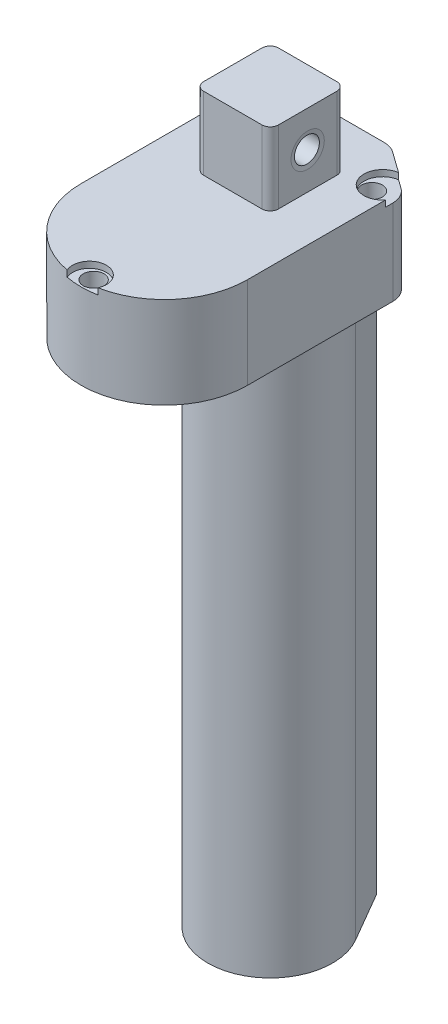
SolidWorks part; units mm, degrees
ref_plane "Alzado" through (0, 0, 0) normal (0, 0, 1) x (1, 0, 0)
ref_plane "Planta" through (0, 0, 0) normal (0, 1, 0) x (1, 0, 0)
ref_plane "Vista lateral" through (0, 0, 0) normal (1, 0, 0) x (0, 0, -1)
sketch "Croquis2" plane through (0, 0, 0) normal (0, 1, 0) x (1, 0, 0)
  line L0 (-17.9062, 38.9956) -> (-10.8039, 44.0687)
  line L1 (0, 0) -> (0, -20) construction
  line L2 (-20, 0) -> (-20, 34.9269)
  line L3 (-7.8977, 45) -> (7.8977, 45)
  line L4 (20, 0) -> (20, 34.9269)
  line L19 (10.8039, 44.0687) -> (17.9062, 38.9956)
  arc A0 (-20, 0) -> (20, 0) centre (0, 0) ccw
  arc A1 (-20, 34.9269) -> (-17.9062, 38.9956) centre (-15, 34.9269) cw
  arc A2 (17.9062, 38.9956) -> (20, 34.9269) centre (15, 34.9269) cw
  arc A3 (10.8039, 44.0687) -> (7.8977, 45) centre (7.8977, 40) ccw
  arc A4 (-7.8977, 45) -> (-10.8039, 44.0687) centre (-7.8977, 40) ccw
  point P1 (0, 45)
  dimension "D1" = 5
  dimension "D2" = 20
  dimension "D3" = 5
  dimension "D4" = 5
  dimension "D5" = 65
extrude "Saliente-Extruir1" add sketch "Croquis2" along normal blind 22
sketch "Croquis3" plane through (0, 22, 0) normal (0, 1, 0) x (1, 0, 0)
  circle A0 centre (-15, 34.9269) radius 2.5
  circle A1 centre (15, 34.9269) radius 2.5
  circle A2 centre (-16.5, 36) radius 4.5
  circle A3 centre (16.5, 36) radius 4.5
extrude "Cortar-Extruir2" cut sketch "Croquis3" against normal blind 1.5
sketch "Croquis4" plane through (0, 22, 0) normal (0, 1, 0) x (1, 0, 0)
  circle A0 centre (-15, 34.9269) radius 2.5
  circle A1 centre (15, 34.9269) radius 2.5
extrude "Cortar-Extruir3" cut sketch "Croquis4" against normal blind 18
sketch "Croquis5" plane through (0, 22, 0) normal (0, 1, 0) x (1, 0, 0)
  line L0 (0, -20) -> (0, -17)
  arc A0 (-20, 0) -> (20, 0) centre (0, 0) ccw construction
  circle A1 centre (0, -17) radius 2.5
  circle A3 centre (0.022, -18) radius 4.0586
extrude "Cortar-Extruir4" cut sketch "Croquis5" against normal blind 1.5 contours A3
sketch "Croquis6" plane through (0, 20.5, 0) normal (0, 1, 0) x (1, 0, 0)
  circle A1 centre (0.0245, -17) radius 2.5
extrude "Cortar-Extruir5" cut sketch "Croquis6" against normal blind 15
sketch "Croquis7" plane through (0, 20.5, 0) normal (0, 1, 0) x (1, 0, 0)
  line L0 (0.0245, -20) -> (0.0245, -16.2667) construction
  line L2 (7.0037, 16.4602) -> (-7.0037, 16.4602)
  line L3 (9.0037, 18.4602) -> (9.0037, 32.4653)
  line L4 (7.0037, 34.4653) -> (-7.0037, 34.4653)
  line L5 (-9.0037, 18.4602) -> (-9.0037, 32.4653)
  line L6 (9.0037, 16.4602) -> (-9.0037, 34.4653) construction
  line L11 (9.0037, 34.4653) -> (-9.0037, 16.4602) construction
  arc A0 (-3.6825, -19.6581) -> (3.7305, -19.649) centre (0, 0) ccw construction
  arc A1 (-9.0037, 18.4602) -> (-7.0037, 16.4602) centre (-7.0037, 18.4602) ccw
  arc A2 (9.0037, 18.4602) -> (7.0037, 16.4602) centre (7.0037, 18.4602) cw
  arc A3 (7.0037, 34.4653) -> (9.0037, 32.4653) centre (7.0037, 32.4653) cw
  arc A4 (-7.0037, 34.4653) -> (-9.0037, 32.4653) centre (-7.0037, 32.4653) ccw
  point P5 (0, 25.4628)
  point P28 (0, 25.4628)
  dimension "D1" = 2
extrude "Saliente-Extruir2" add sketch "Croquis7" along normal blind 19
sketch "Croquis8" plane through (-9.0037, 0, 0) normal (-1, 0, 0) x (0, 0, 1)
  line L0 (-25.4628, 39.5) -> (-25.4628, 22) construction
  line L1 (-32.4653, 39.5) -> (-18.4602, 39.5) construction
  line L2 (-18.4602, 22) -> (-32.4653, 22) construction
  line L3 (-32.4653, 30.75) -> (-18.4602, 30.75) construction
  line L4 (-32.4653, 39.5) -> (-32.4653, 22) construction
  line L5 (-18.4602, 39.5) -> (-18.4602, 22) construction
  circle A1 centre (-25.4628, 30.75) radius 3
extrude "Cortar-Extruir7" cut sketch "Croquis8" against normal blind 19
sketch "Croquis9" plane through (-9.0037, 0, 0) normal (-1, 0, 0) x (0, 0, 1)
  circle A0 centre (-25.4628, 30.75) radius 4
extrude "Cortar-Extruir10" cut sketch "Croquis9" against normal blind 0.5 draft 80
sketch "Croquis10" plane through (9.0037, 0, 0) normal (1, 0, 0) x (0, 0, -1)
  circle A0 centre (25.4628, 30.75) radius 4
extrude "Cortar-Extruir11" cut sketch "Croquis10" against normal blind 0.5 draft 80
sketch "Croquis11" plane through (0, 0, 0) normal (0, -1, 0) x (1, 0, 0)
  line L0 (0, 0) -> (0, -50.9255) construction
  line L1 (-20, -34.9269) -> (-20, 0) construction
  line L2 (0, -16.4602) -> (0, -34.4653) construction
  line L4 (-6, -45) -> (-12.9713, -32.9957)
  line L5 (-6, -45) -> (6, -45)
  line L6 (6, -45) -> (12.9713, -32.9957)
  line L7 (7.0037, -16.4602) -> (-7.0037, -16.4602) construction
  line L8 (7.8977, -45) -> (-7.8977, -45) construction
  line L9 (-7.0037, -34.4653) -> (7.0037, -34.4653) construction
  line L10 (-9.0037, -25.4628) -> (8.8273, -25.4628) construction
  line L11 (-9.0037, -18.4602) -> (-9.0037, -32.4653) construction
  line L12 (8.8273, -28.4628) -> (8.8273, -22.4628) construction
  arc A1 (12.9713, -32.9957) -> (-12.9713, -32.9957) centre (0, -25.4628) ccw
  dimension "D1" = 12
  dimension "D2" = 30
  dimension "D3" = 0
  dimension "D4" = 20
  dimension "D5" = 6
extrude "Saliente-Extruir3" add sketch "Croquis11" along normal blind 135.5
sketch "Croquis12" plane through (0, -135.5, 0) normal (0, -1, 0) x (1, 0, 0)
  line L0 (0, -16.4602) -> (0, -34.4653) construction
  line L1 (7.0037, -16.4602) -> (-7.0037, -16.4602) construction
  line L2 (-7.0037, -34.4653) -> (7.0037, -34.4653) construction
  line L3 (0, -25.4628) -> (10.6556, -25.4628) construction
  circle A0 centre (0, -25.4628) radius 10
  dimension "D1" = 20
extrude "Cortar-Extruir12" cut sketch "Croquis12" against normal blind 100
sketch "Croquis14" plane through (0, 0, -34.4653) normal (0, 0, -1) x (-1, 0, 0)
  line L0 (7.0037, 39.5) -> (58.9802, 39.5) construction
  line L1 (0, -135.5) -> (58.9802, -135.5) construction
  line L2 (6, -135.5) -> (-6, -135.5) construction
  line L3 (20, 22) -> (33.0681, 22) construction
  line L4 (7.0037, 30.75) -> (58.9802, 30.75) construction
  line L5 (7.0037, 39.5) -> (7.0037, 22) construction
  dimension "D1" = 166.25
  dimension "D2" = 17.5
